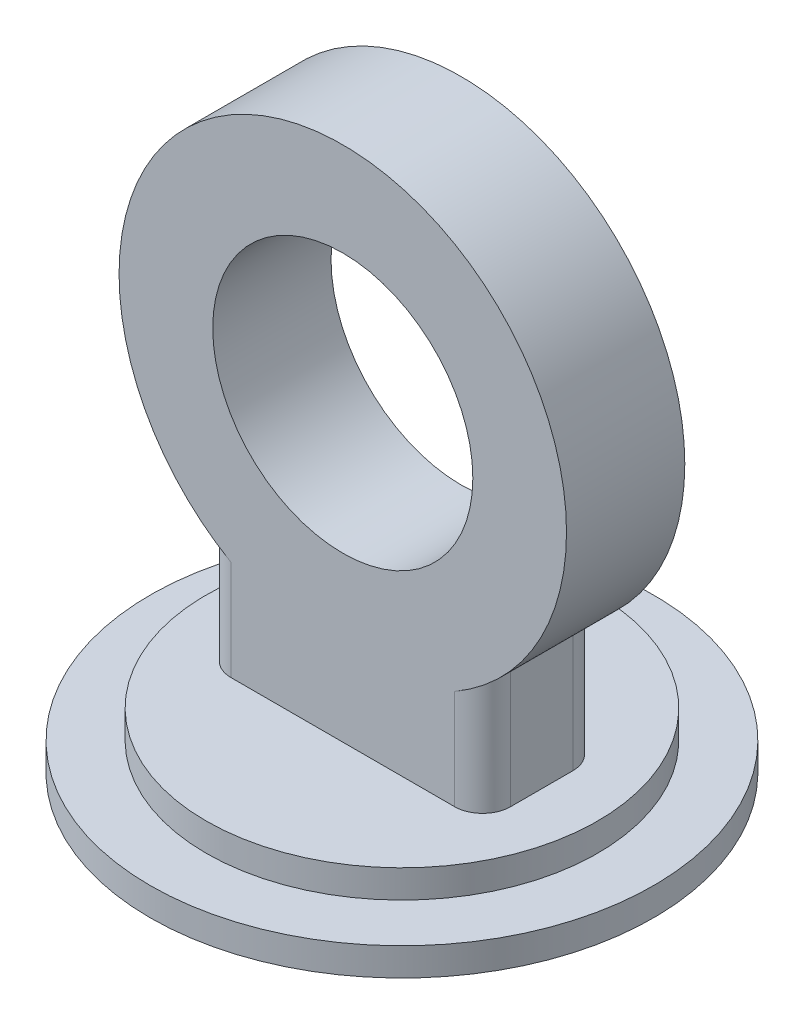
SolidWorks part; units mm, degrees
ref_plane "前视基准面" through (0, 0, 0) normal (0, 0, 1) x (1, 0, 0)
ref_plane "上视基准面" through (0, 0, 0) normal (0, 1, 0) x (1, 0, 0)
ref_plane "右视基准面" through (0, 0, 0) normal (1, 0, 0) x (0, 0, -1)
other "Configuration Table"
sketch "草图1" plane through (0, 0, 0) normal (0, 1, 0) x (1, 0, 0)
  circle A0 centre (0, 0) radius 90
  dimension "D1" = 180
extrude "凸台-拉伸1" add sketch "草图1" along normal blind 10
sketch "草图2" plane through (0, 10, 0) normal (0, 1, 0) x (1, 0, 0)
  circle A0 centre (0, 0) radius 70
  dimension "D1" = 140
extrude "凸台-拉伸2" add sketch "草图2" along normal blind 10
sketch "草图4" plane through (0, 0, 0) normal (0, 0, 1) x (1, 0, 0)
  circle A0 centre (0, 125) radius 46.5
  circle A1 centre (0, 125) radius 80
  dimension "D1" = 93
  dimension "D2" = 160
  dimension "D3" = 105
extrude "凸台-拉伸3" add sketch "草图4" along normal mid plane 42.3 separate body
sketch "草图5" plane through (0, 20, 0) normal (0, 1, 0) x (1, 0, 0)
  line L1 (-50, 21.15) -> (50, 21.15)
  line L2 (-50, 21.15) -> (-50, -21.15)
  line L3 (-50, -21.15) -> (50, -21.15)
  line L4 (50, 21.15) -> (50, -21.15)
  line L5 (-50, 21.15) -> (50, -21.15) construction
  line L6 (-50, -21.15) -> (50, 21.15) construction
  point P0 (0, 0)
  dimension "D1" = 42.3
  dimension "D2" = 100
extrude "凸台-拉伸4" add sketch "草图5" along normal up to next
fillet "圆角1" radius 10 4 edges at (-50, 41.275, 21.15) (-50, 41.275, -21.15) (50, 41.275, 21.15) (50, 41.275, -21.15)
sketch "草图6" plane through (0, 0, 0) normal (0, -1, 0) x (1, 0, 0)
  circle A0 centre (0, 0) radius 46.5
  dimension "D1" = 93
extrude "切除-拉伸1" cut sketch "草图6" against normal blind 1
